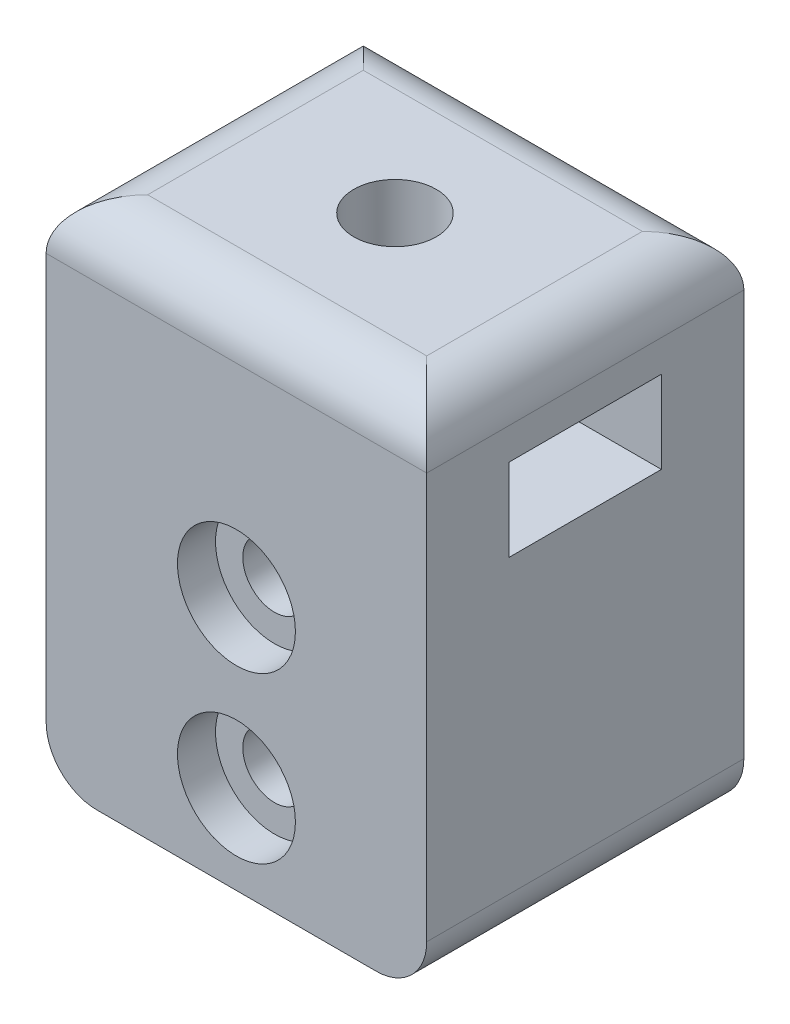
SolidWorks part; units mm, degrees
ref_plane "Alzado" through (0, 0, 0) normal (0, 0, 1) x (1, 0, 0)
ref_plane "Planta" through (0, 0, 0) normal (0, 1, 0) x (1, 0, 0)
ref_plane "Vista lateral" through (0, 0, 0) normal (1, 0, 0) x (0, 0, -1)
sketch "Croquis1" plane through (0, 0, 0) normal (0, 1, 0) x (1, 0, 0)
  line L0 (-8.75, 9.55) -> (21.25, 9.55)
  line L1 (21.25, -15.45) -> (-8.75, -15.45)
  line L5 (-8.75, 9.55) -> (-8.75, -15.45)
  line L7 (21.25, 9.55) -> (21.25, -15.45)
  dimension "D2" = 25
  dimension "D3" = 30
extrude "Saliente-Extruir1" add sketch "Croquis1" along normal blind 20
sketch "Croquis2" plane through (0, 20, 0) normal (0, 1, 0) x (1, 0, 0)
  line L16 (-8.75, 9.55) -> (-8.75, -15.45)
  line L19 (21.25, 9.55) -> (21.25, -15.45)
  line L22 (-8.75, -15.45) -> (21.25, -15.45)
  line L23 (21.25, 9.55) -> (-8.75, 9.55)
  line L24 (21.25, -15.45) -> (21.25, 9.55) construction
  line L25 (-8.75, 9.55) -> (-8.75, -15.45) construction
  point P16 (-6, 0)
extrude "Saliente-Extruir2" add sketch "Croquis2" along normal blind 20
sketch "Croquis3" plane through (-8.75, 0, 0) normal (-1, 0, 0) x (0, 0, 1)
  line L0 (-3.05, 33.5) -> (-3.05, 27)
  line L2 (-3.05, 27) -> (8.95, 27)
  line L3 (8.95, 27) -> (8.95, 33.5)
  line L4 (2.95, 0) -> (2.95, 27) construction
  line L5 (-9.55, 0) -> (15.45, 0) construction
  line L6 (-3.05, 33.5) -> (8.95, 33.5)
  point P11 (2.95, 27)
  dimension "D1" = 12
  dimension "D2" = 6.5
  dimension "D3" = 27
extrude "Cortar-Extruir1" cut sketch "Croquis3" against normal up to next
sketch "Croquis5" plane through (0, 0, 0) normal (0, -1, 0) x (1, 0, 0)
  line L0 (6.25, 15.45) -> (6.25, 8.45) construction
  line L1 (-8.75, 15.45) -> (21.25, 15.45) construction
  line L2 (6.25, -9.55) -> (6.25, 0.45) construction
  line L3 (21.25, -9.55) -> (-8.75, -9.55) construction
  line L4 (1.5, 8.45) -> (11, 8.45)
  line L5 (1.5, 8.45) -> (1.5, 4.95)
  line L6 (1.5, 4.95) -> (11, 4.95)
  line L7 (11, 8.45) -> (11, 4.95)
  circle A0 centre (6.25, 0.45) radius 3.5
  point P10 (6.25, 8.45)
  point P11 (6.25, 15.45)
  dimension "D5" = 7
  dimension "D1" = 7
  dimension "D2" = 9.5
  dimension "D3" = 10
  dimension "D4" = 3.5
extrude "Cortar-Extruir3" cut sketch "Croquis5" against normal blind 25
sketch "Croquis6" plane through (0, 0, 15.45) normal (0, 0, 1) x (1, 0, 0)
  line L0 (6.25, 0) -> (6.25, 7) construction
  line L2 (-8.75, 0) -> (21.25, 0) construction
  circle A0 centre (6.25, 7) radius 4.65
  circle A1 centre (6.25, 20) radius 4.65
  point P2 (0, 0)
  point P3 (0, 0)
  dimension "D1" = 9.3
  dimension "D2" = 9.3
  dimension "D3" = 13
  dimension "D4" = 7
extrude "Cortar-Extruir4" cut sketch "Croquis6" against normal blind 3
sketch "Croquis7" plane through (0, 0, 12.45) normal (0, 0, 1) x (1, 0, 0)
  circle A0 centre (6.25, 20) radius 2.5
  circle A1 centre (6.25, 7) radius 2.5
  dimension "D1" = 5
  dimension "D2" = 5
extrude "Cortar-Extruir5" cut sketch "Croquis7" against normal up to surface (9.5505 mm away)
fillet "Redondeo4" radius 4 2 edges at (-8.75, 0, 2.95) (21.25, 0, 2.95)
sketch "Croquis8" plane through (0, 33.5, 0) normal (0, -1, 0) x (1, 0, 0)
  line L0 (6.25, 8.95) -> (6.25, -3.05) construction
  line L1 (21.25, 8.95) -> (-8.75, 8.95) construction
  line L2 (21.25, -3.05) -> (-8.75, -3.05) construction
  circle A0 centre (6.25, 2.95) radius 3.25
  dimension "D1" = 6.5
extrude "Cortar-Extruir6" cut sketch "Croquis8" against normal mid plane 19
fillet "Redondeo5" radius 4 4 edges at (6.25, 40, -9.55) (6.25, 40, 15.45) (-8.75, 40, 2.95) (21.25, 40, 2.95)
